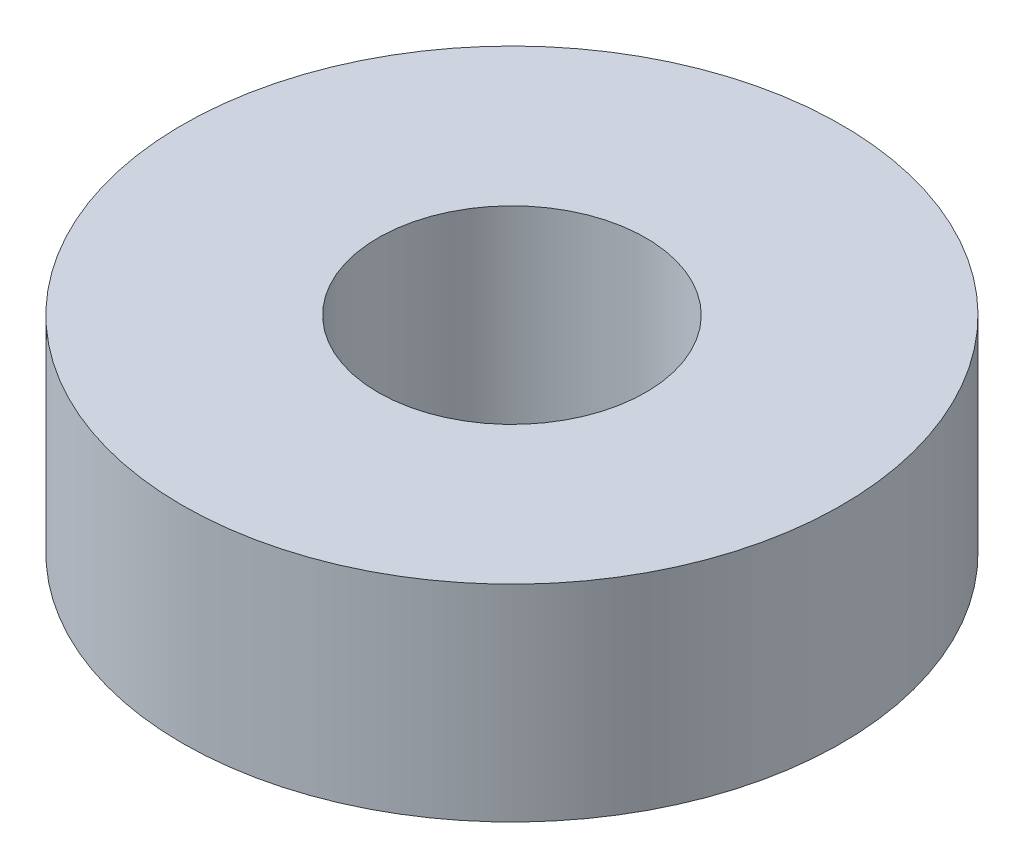
SolidWorks part; units mm, degrees
ref_plane "Front Plane" through (0, 0, 0) normal (0, 0, 1) x (1, 0, 0)
ref_plane "Top Plane" through (0, 0, 0) normal (0, 1, 0) x (1, 0, 0)
ref_plane "Right Plane" through (0, 0, 0) normal (1, 0, 0) x (0, 0, -1)
sketch "Sketch1" plane through (0, 0, 0) normal (0, 1, 0) x (1, 0, 0)
  circle A0 centre (0, 0) radius 24
  circle A1 centre (0, 0) radius 9.75
  dimension "D1" = 48
  dimension "D2" = 19.5
extrude "Boss-Extrude1" add sketch "Sketch1" along normal blind 15
